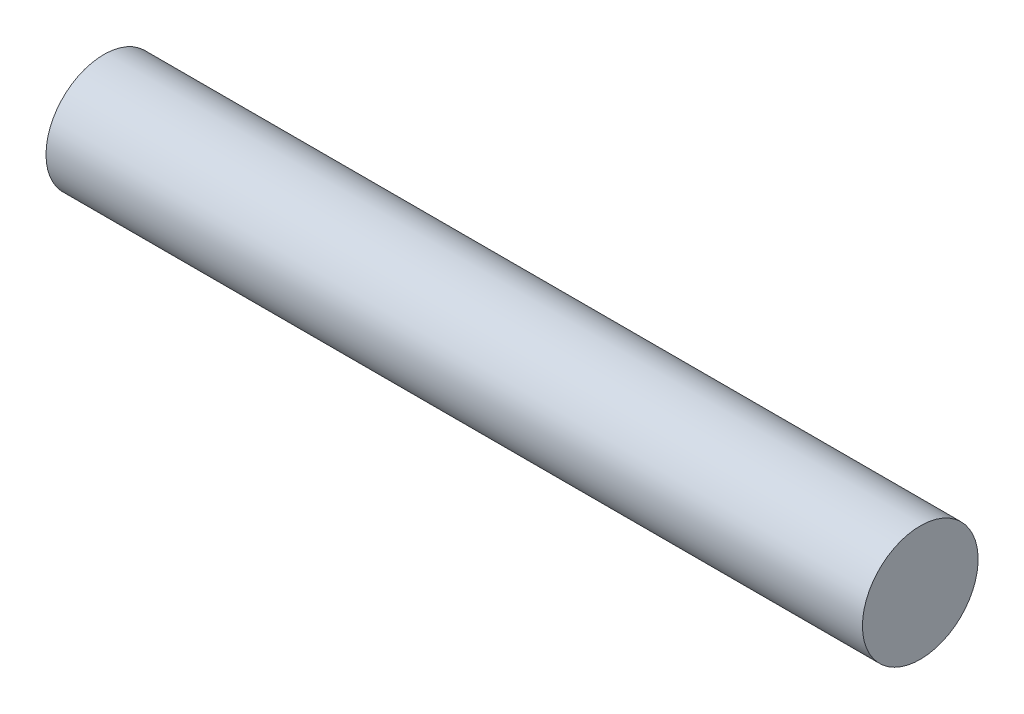
SolidWorks part; units mm, degrees
ref_plane "Front Plane" through (0, 0, 0) normal (0, 0, 1) x (1, 0, 0)
ref_plane "Top Plane" through (0, 0, 0) normal (0, 1, 0) x (1, 0, 0)
ref_plane "Right Plane" through (0, 0, 0) normal (1, 0, 0) x (0, 0, -1)
sketch "Sketch2" plane through (0, 0, 0) normal (0, 1, 0) x (1, 0, 0)
  line L0 (0, 0) -> (900, 0)
  line L1 (900, 0) -> (900, 63.75)
  line L2 (900, 63.75) -> (0, 63.75)
  line L3 (0, 63.75) -> (0, 0)
revolve "Revolve1" add sketch "Sketch2" angle 360 about L2
